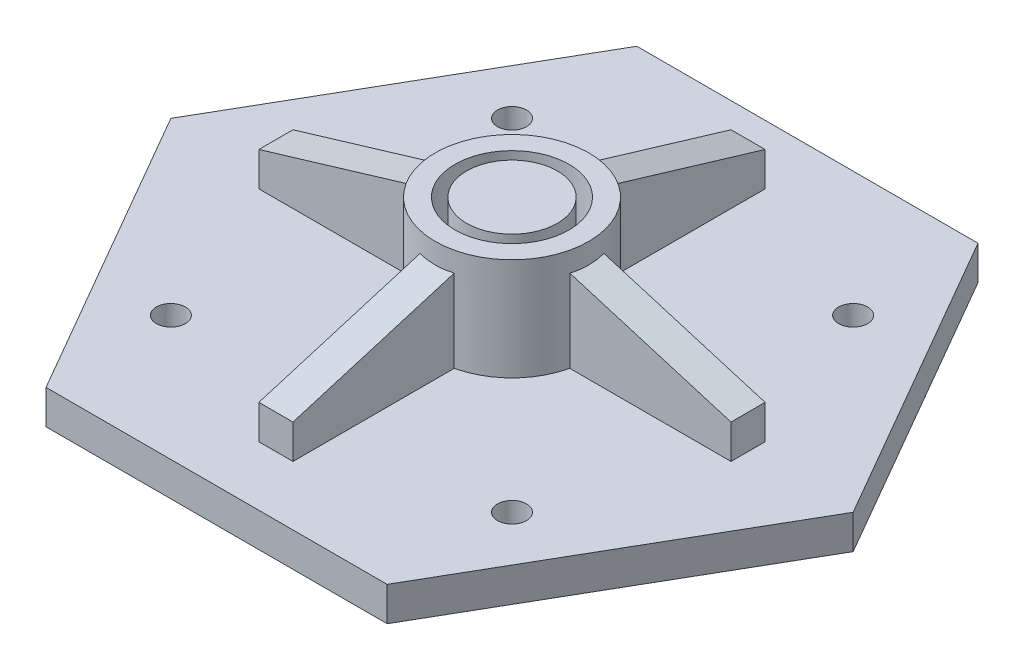
SolidWorks part; units mm, degrees
material "ABS"
ref_plane "Alzado" through (0, 0, 0) normal (0, 0, 1) x (1, 0, 0)
ref_plane "Planta" through (0, 0, 0) normal (0, 1, 0) x (1, 0, 0)
ref_plane "Vista lateral" through (0, 0, 0) normal (1, 0, 0) x (0, 0, -1)
sketch "Croquis1" plane through (0, 0, 0) normal (0, 1, 0) x (1, 0, 0)
  circle A0 centre (0, 0) radius 22.5
  dimension "D1" = 45
extrude "Saliente-Extruir1" add sketch "Croquis1" along normal blind 40
sketch "Croquis2" plane through (0, 40, 0) normal (0, 1, 0) x (1, 0, 0)
  circle A0 centre (0, 0) radius 16.7
  circle A1 centre (0, 0) radius 13.3
  dimension "D1" = 33.4
  dimension "D2" = 3.4
extrude "Cortar-Extruir1" cut sketch "Croquis2" against normal blind 30
sketch "Croquis3" plane through (0, 0, 0) normal (0, -1, 0) x (1, 0, 0)
  line L1 (50, 86.6025) -> (-50, 86.6025)
  line L2 (-50, 86.6025) -> (-100, 0)
  line L3 (-100, 0) -> (-50, -86.6025)
  line L4 (-50, -86.6025) -> (50, -86.6025)
  line L5 (50, -86.6025) -> (100, 0)
  line L6 (100, 0) -> (50, 86.6025)
  circle A0 centre (0, 0) radius 86.6025 construction
  dimension "D1" = 200
extrude "Saliente-Extruir2" add sketch "Croquis3" against normal blind 10
sketch "Croquis4" plane through (0, 0, 0) normal (1, 0, 0) x (0, 0, -1)
  line L3 (0, 10) -> (-86.6025, 10) construction
  line L4 (-69.2, 10) -> (-19.2, 10)
  line L5 (-19.2, 10) -> (-19.2, 35)
  line L6 (22.5, 40) -> (-22.5, 40) construction
  line L7 (-19.2, 35) -> (-69.2, 20)
  line L8 (-69.2, 20) -> (-69.2, 10)
  line L9 (-22.5, 40) -> (-22.5, 10) construction
  dimension "D1" = 5
  dimension "D2" = 50
  dimension "D3" = 10
  dimension "D4" = 3.3
extrude "Saliente-Extruir5" add sketch "Croquis4" along normal mid plane 10
pattern_circular "MatrizC1" count 4 over 360 about axis through (0, 0, 0) along (0, 1, 0) of "Saliente-Extruir5"
sketch "Croquis5" plane through (0, 10, 0) normal (0, 1, 0) x (1, 0, 0)
  line L1 (-50, -50) -> (50, -50) construction
  line L2 (-50, -50) -> (-50, 50) construction
  line L3 (-50, 50) -> (50, 50) construction
  line L4 (50, -50) -> (50, 50) construction
  line L5 (-50, -50) -> (50, 50) construction
  line L6 (-50, 50) -> (50, -50) construction
  circle A0 centre (-50, 50) radius 4.25
  circle A1 centre (50, 50) radius 4.25
  circle A2 centre (-50, -50) radius 4.25
  circle A3 centre (50, -50) radius 4.25
  point P0 (0, 0)
  dimension "D3" = 8.5
  dimension "D1" = 100
  dimension "D2" = 100
extrude "Cortar-Extruir2" cut sketch "Croquis5" against normal through all
